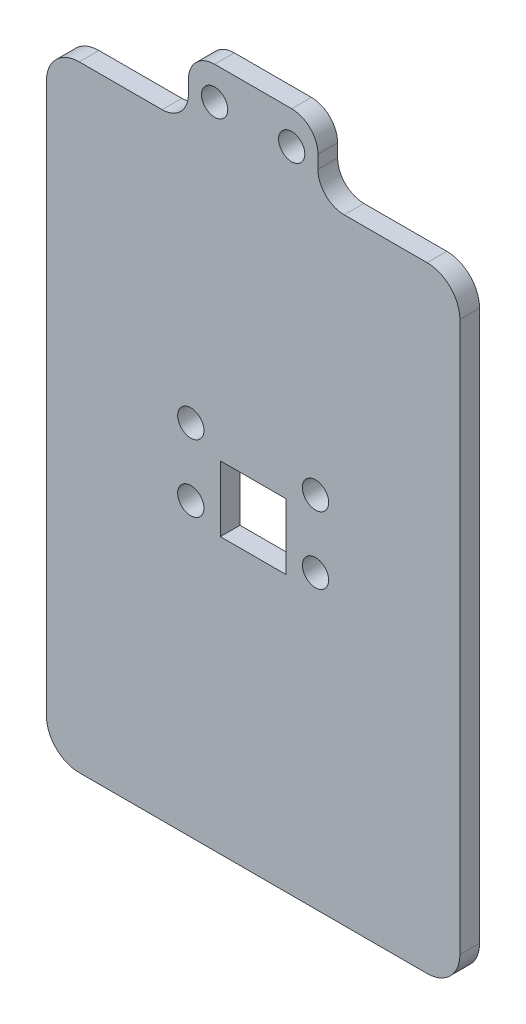
SolidWorks part; units mm, degrees
ref_plane "Спереди" through (0, 0, 0) normal (0, 0, 1) x (1, 0, 0)
ref_plane "Сверху" through (0, 0, 0) normal (0, 1, 0) x (1, 0, 0)
ref_plane "Справа" through (0, 0, 0) normal (1, 0, 0) x (0, 0, -1)
sketch "Эскиз1" plane through (0, 0, 0) normal (0, 0, 1) x (1, 0, 0)
  line L0 (13.8697, 46.9) -> (26.5, 46.9)
  line L1 (-26.5, -46.9) -> (26.5, -46.9)
  line L2 (-31.5, -41.9) -> (-31.5, 41.9)
  line L3 (-26.5, 46.9) -> (-13.8697, 46.9)
  line L4 (31.5, -41.9) -> (31.5, 41.9)
  line L5 (-31.5, -46.9) -> (31.5, 46.9) construction
  line L6 (-31.5, 46.9) -> (31.5, -46.9) construction
  line L7 (-5, 5) -> (5, 5)
  line L8 (-5, 5) -> (-5, -5)
  line L9 (-5, -5) -> (5, -5)
  line L10 (5, 5) -> (5, -5)
  line L11 (-5, 5) -> (5, -5) construction
  line L12 (-5, -5) -> (5, 5) construction
  line L13 (-5.8697, 56.9) -> (5.8697, 56.9)
  line L14 (-9.8697, 52.9) -> (-9.8697, 50.9)
  line L15 (-9.8697, 51.9) -> (9.8697, 51.9) construction
  line L16 (9.8697, 52.9) -> (9.8697, 50.9)
  line L18 (-12.5, -12) -> (12.5, -12) construction
  line L19 (-12.5, -12) -> (-12.5, 12) construction
  line L20 (-12.5, 12) -> (12.5, 12) construction
  line L21 (12.5, -12) -> (12.5, 12) construction
  line L22 (-12.5, -12) -> (12.5, 12) construction
  line L23 (-12.5, 12) -> (12.5, -12) construction
  arc A0 (-26.5, -46.9) -> (-31.5, -41.9) centre (-26.5, -41.9) cw
  arc A1 (26.5, -46.9) -> (31.5, -41.9) centre (26.5, -41.9) ccw
  arc A2 (26.5, 46.9) -> (31.5, 41.9) centre (26.5, 41.9) cw
  arc A3 (-31.5, 41.9) -> (-26.5, 46.9) centre (-26.5, 41.9) cw
  arc A4 (5.8697, 56.9) -> (9.8697, 52.9) centre (5.8697, 52.9) cw
  arc A5 (-5.8697, 56.9) -> (-9.8697, 52.9) centre (-5.8697, 52.9) ccw
  arc A6 (13.8697, 46.9) -> (9.8697, 50.9) centre (13.8697, 50.9) cw
  arc A7 (-9.8697, 50.9) -> (-13.8697, 46.9) centre (-13.8697, 50.9) cw
  circle A8 centre (-5.8697, 51.9) radius 2
  circle A9 centre (5.8697, 51.9) radius 2
  circle A10 centre (9.5, -2.5) radius 2
  circle A11 centre (-9.5, -2.5) radius 2
  circle A12 centre (-9.5, 7.75) radius 2
  circle A13 centre (9.5, 7.75) radius 2
  point P0 (0, 0)
  point P6 (0, 0)
  point P27 (0, 46.9)
  point P30 (9.8697, 56.9)
  point P35 (9.8697, 46.9)
  point P48 (0, 0)
  dimension "D3" = 5
  dimension "D5" = 4
  dimension "D6" = 4
  dimension "D8" = 4
  dimension "D11" = 9.5
  dimension "D12" = 4.5
  dimension "D16" = 10.25
  dimension "D1" = 93.8
  dimension "D2" = 63
  dimension "D4" = 10
  dimension "D7" = 10
  dimension "D9" = 4.5
  dimension "D10" = 9.5
  dimension "D13" = 25
  dimension "D14" = 24
  dimension "D15" = 10.25
extrude "Бобышка-Вытянуть1" add sketch "Эскиз1" along normal blind 3
